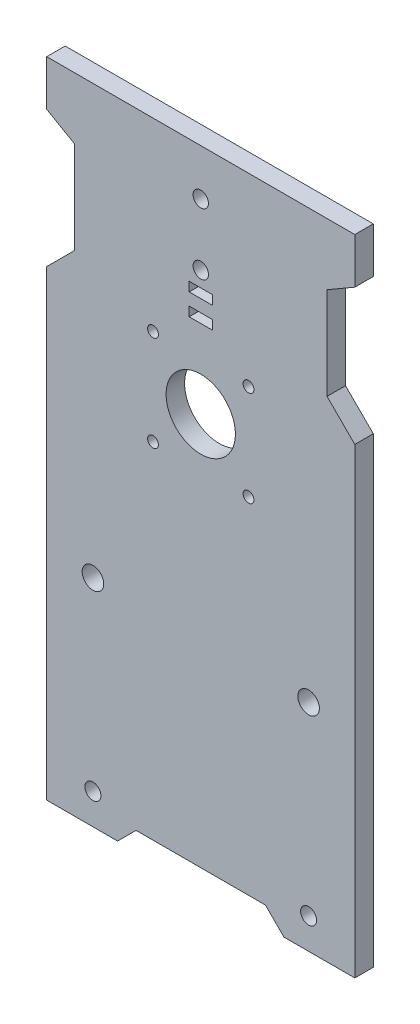
SolidWorks part; units mm, degrees
ref_plane "Alzado" through (0, 0, 0) normal (0, 0, 1) x (1, 0, 0)
ref_plane "Planta" through (0, 0, 0) normal (0, 1, 0) x (1, 0, 0)
ref_plane "Vista lateral" through (0, 0, 0) normal (1, 0, 0) x (0, 0, -1)
sketch "Croquis1" plane through (0, 0, 0) normal (0, 0, 1) x (1, 0, 0)
  line L0 (-50, -104.5) -> (-50, 45.5)
  line L1 (-50, 45.5) -> (-41, 54.5)
  line L2 (-41, 54.5) -> (-41, 84.5)
  line L3 (-41, 84.5) -> (-50, 89.6962)
  line L4 (-50, 89.6962) -> (-50, 104.5)
  line L5 (-50, 104.5) -> (50, 104.5)
  line L6 (50, 104.5) -> (50, 89.6962)
  line L7 (50, 89.6962) -> (41, 84.5)
  line L8 (41, 84.5) -> (41, 54.5)
  line L9 (41, 54.5) -> (50, 45.5)
  line L10 (50, 45.5) -> (50, -104.5)
  line L11 (50, -104.5) -> (27, -104.5)
  line L12 (27, -104.5) -> (21, -98.5)
  line L13 (21, -98.5) -> (-21, -98.5)
  line L14 (-21, -98.5) -> (-27, -104.5)
  line L15 (-27, -104.5) -> (-50, -104.5)
  line L16 (-3.75, 54.5) -> (3.75, 54.5)
  line L17 (-3.75, 54.5) -> (-3.75, 57.5)
  line L18 (-3.75, 57.5) -> (3.75, 57.5)
  line L19 (3.75, 54.5) -> (3.75, 57.5)
  line L20 (-3.75, 61.5) -> (3.75, 61.5)
  line L21 (-3.75, 61.5) -> (-3.75, 64.5)
  line L22 (-3.75, 64.5) -> (3.75, 64.5)
  line L23 (3.75, 61.5) -> (3.75, 64.5)
  circle A0 centre (-35, -94.5) radius 2.6
  circle A1 centre (-35, -34.5) radius 3.5
  circle A2 centre (35, -34.5) radius 3.5
  circle A3 centre (35, -94.5) radius 2.6
  circle A4 centre (-15.5, 13.5) radius 1.75
  circle A5 centre (15.5, 13.5) radius 1.75
  circle A6 centre (0, 29) radius 11.25
  circle A7 centre (15.5, 44.5) radius 1.75
  circle A8 centre (-15.5, 44.5) radius 1.75
  circle A9 centre (0, 69.5) radius 2.5
  circle A10 centre (0, 89.5) radius 2.5
extrude "Saliente-Extruir1" add sketch "Croquis1" along normal blind 6
